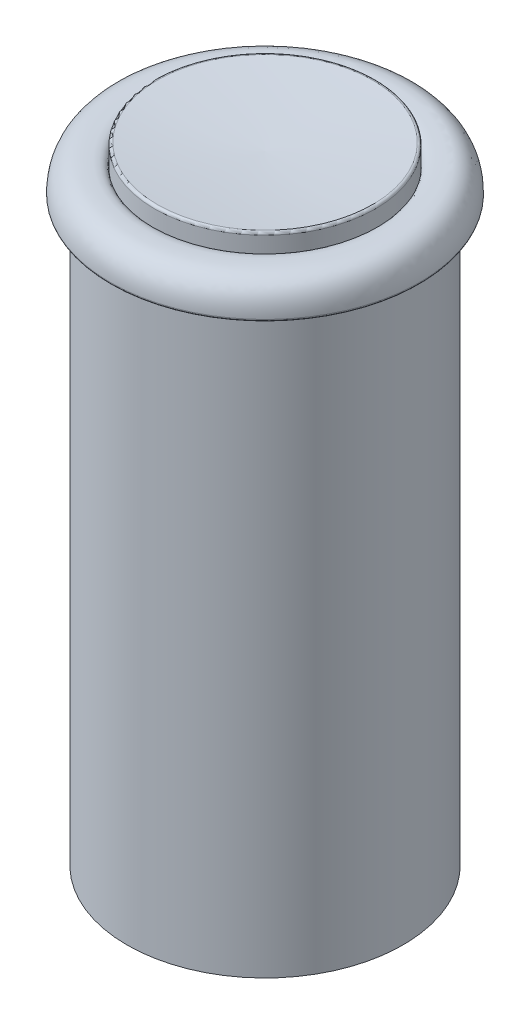
SolidWorks part; units mm, degrees
ref_plane "Front Plane" through (0, 0, 0) normal (0, 0, 1) x (1, 0, 0)
ref_plane "Top Plane" through (0, 0, 0) normal (0, 1, 0) x (1, 0, 0)
ref_plane "Right Plane" through (0, 0, 0) normal (1, 0, 0) x (0, 0, -1)
sketch "Sketch1" plane through (0, 0, 0) normal (0, 1, 0) x (1, 0, 0)
  circle A0 centre (0, 0) radius 16
  dimension "D1" = 32
extrude "Boss-Extrude1" add sketch "Sketch1" along normal blind 65
sketch "Sketch2" plane through (0, 0, 0) normal (0, 0, 1) x (1, 0, 0)
  line L0 (0, 65) -> (0, 0) construction
  line L1 (16, 65) -> (-16, 65) construction
  line L2 (16, 0) -> (16, 65) construction
  line L3 (16, 60) -> (14.2875, 60)
  line L4 (16, 60) -> (16, 0)
  line L5 (16, 0) -> (14.2875, 0)
  line L6 (14.2875, 60) -> (14.2875, 0)
  line L7 (-16, 0) -> (16, 0) construction
  line L8 (11.43, 64.8543) -> (11.43, 62.5)
  line L9 (0, 65) -> (0, 64.0228)
  line L10 (0, 65) -> (9.3726, 65)
  line L11 (16, 60.1699) -> (16, 65)
  line L12 (16, 65) -> (9.3726, 65)
  line L13 (14.2875, 60) -> (0, 60) construction
  line L14 (11.43, 60) -> (11.43, 65) construction
  line L15 (14.4084, 63.3486) -> (12.5889, 63.3486) construction
  line L16 (11.43, 63.6773) -> (11.43, 61.3227) construction
  line L17 (16, 60.4214) -> (16, 63.6308) construction
  arc A0 (0, 64.0228) -> (11.43, 64.8543) centre (-4.6191, 206.4876) ccw
  spline S0 degree 3 poles (11.43, 62.5) (11.43, 63.3801) (12.6661, 63.3049) (14.3724, 63.3954) (16, 62.5989) (16, 60.1699) knots 0 0 0 0 0.469325 0.569325 1 1 1 1
  point P24 (11.43, 62.5)
  point P25 (13.3264, 64.2828)
  point P26 (0, 0)
  point P34 (16, 60.132)
  point P35 (16, 60.0253)
  point P36 (16, 60.1699)
  point P37 (13.566, 63.3486)
  dimension "D1" = 60
  dimension "D2" = 14.2875
  dimension "D3" = 11.43
revolve "Cut-Revolve1" cut sketch "Sketch2" angle 360 about L0
fillet "Fillet1" radius 0.254 3 edges at (0, 60, 16) (0, 60, 14.2875) (0, 64.8543, 11.43)
